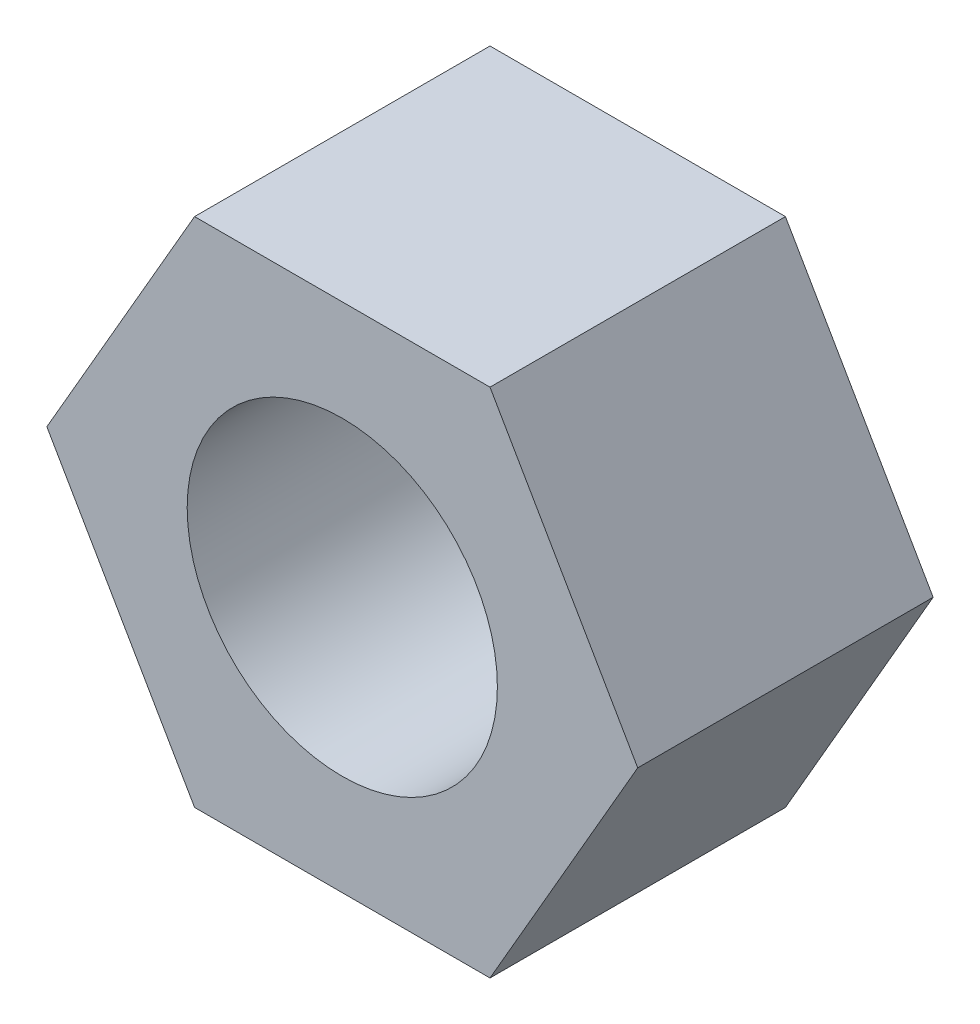
SolidWorks part; units mm, degrees
ref_plane "前视基准面" through (0, 0, 0) normal (0, 0, 1) x (1, 0, 0)
ref_plane "上视基准面" through (0, 0, 0) normal (0, 1, 0) x (1, 0, 0)
ref_plane "右视基准面" through (0, 0, 0) normal (1, 0, 0) x (0, 0, -1)
sketch "草图2" plane through (0, 0, 0) normal (0, 0, 1) x (1, 0, 0)
  line L1 (2, -3.4641) -> (4, 0)
  line L2 (4, 0) -> (2, 3.4641)
  line L3 (2, 3.4641) -> (-2, 3.4641)
  line L4 (-2, 3.4641) -> (-4, 0)
  line L5 (-4, 0) -> (-2, -3.4641)
  line L6 (-2, -3.4641) -> (2, -3.4641)
  circle A0 centre (0, 0) radius 3.4641 construction
  dimension "D1" = 4
extrude "拉伸1" add sketch "草图2" along normal blind 4
hole_wizard "M5x0.8 螺纹孔2" positions "3D草图6" profile "草图9" tap size "M5x0.8" standard "ISO" end condition through all
sketch3d "3D草图6"
  point P0 (0, 0, 0)
sketch "草图9" plane through (0, 0, 0) normal (1, 0, 0) x (0, 1, 0)
  line L0 (0, 0) -> (0, 4)
  line L1 (0, 4) -> (2.1, 4)
  line L2 (2.1, 4) -> (2.1, 0)
  line L5 (2.1, 0) -> (0, 0)
  line L11 (0, -6.35) -> (0, 107.95) construction
  dimension "籵謂蹟恇謂郰芛眻噤" = 4.2
  dimension "籵謂蹟恇謂郰芛旮僅" = 4
cosmetic thread "装饰螺纹线1" parameters "D2"=5
